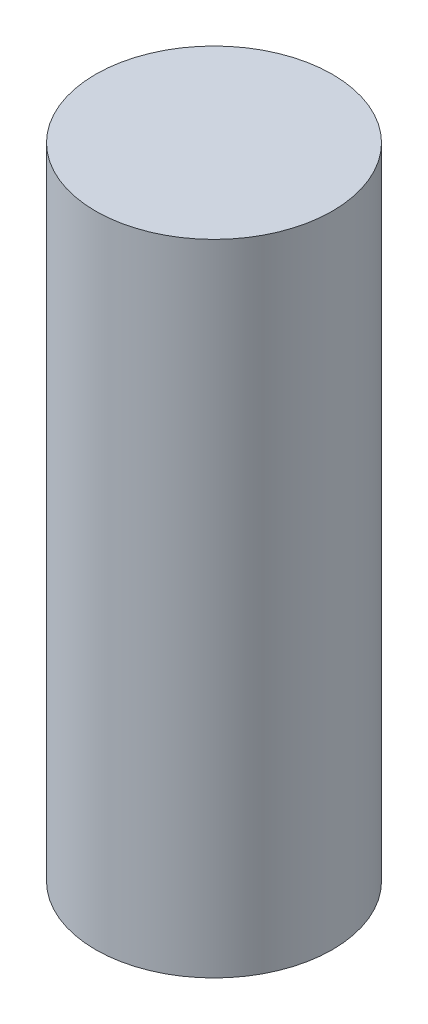
SolidWorks part; units mm, degrees
ref_plane "Front Plane" through (0, 0, 0) normal (0, 0, 1) x (1, 0, 0)
ref_plane "Top Plane" through (0, 0, 0) normal (0, 1, 0) x (1, 0, 0)
ref_plane "Right Plane" through (0, 0, 0) normal (1, 0, 0) x (0, 0, -1)
sketch "Sketch1" plane through (0, 0, 0) normal (0, 1, 0) x (1, 0, 0)
  circle A0 centre (0, 0) radius 5
  dimension "D1" = 10
extrude "Boss-Extrude1" add sketch "Sketch1" along normal blind 27
